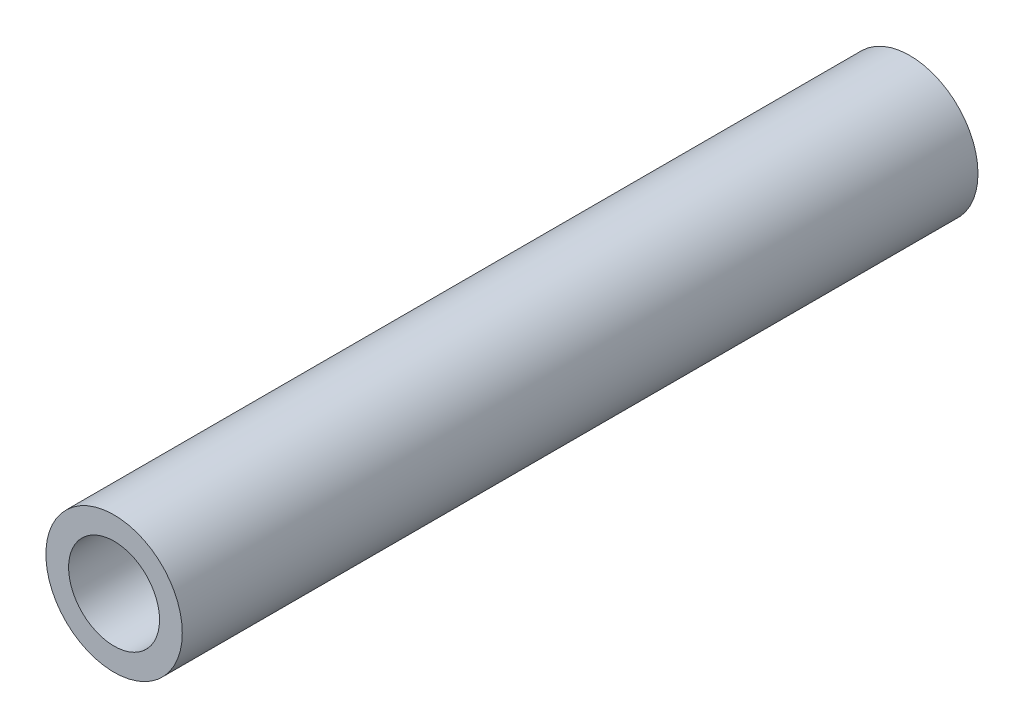
SolidWorks part; units mm, degrees
ref_plane "Front Plane" through (0, 0, 0) normal (0, 0, 1) x (1, 0, 0)
ref_plane "Top Plane" through (0, 0, 0) normal (0, 1, 0) x (1, 0, 0)
ref_plane "Right Plane" through (0, 0, 0) normal (1, 0, 0) x (0, 0, -1)
sketch "Sketch1" plane through (0, 0, 0) normal (0, 0, 1) x (1, 0, 0)
  circle A0 centre (6, 6) radius 3
  dimension "D2" = 6
extrude "Boss-Extrude1" add sketch "Sketch1" along normal blind 35 contours A0
sketch "Sketch2" plane through (0, 0, 35) normal (0, 0, 1) x (1, 0, 0)
  circle A0 centre (6, 6) radius 2
  dimension "D1" = 4
extrude "Cut-Extrude1" cut sketch "Sketch2" against normal blind 30 contours A0
